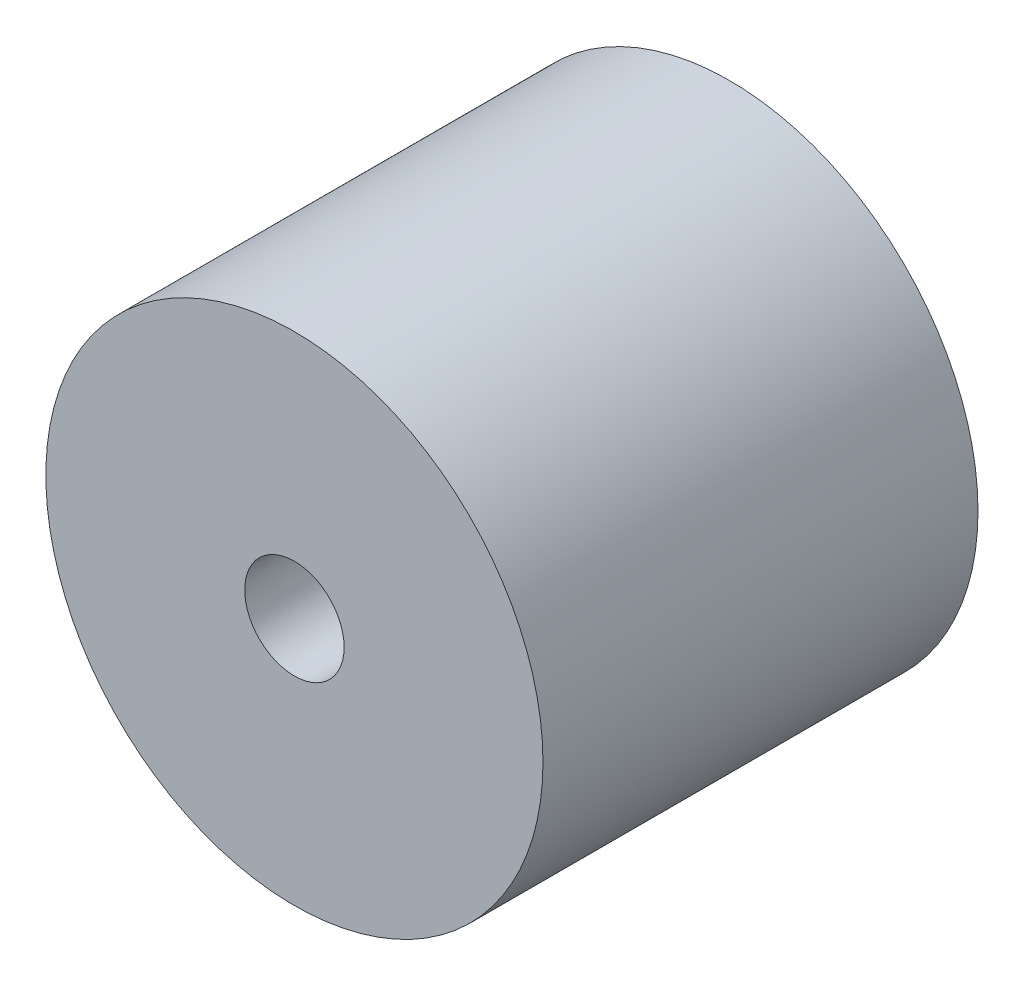
SolidWorks part; units mm, degrees
ref_plane "Front Plane" through (0, 0, 0) normal (0, 0, 1) x (1, 0, 0)
ref_plane "Top Plane" through (0, 0, 0) normal (0, 1, 0) x (1, 0, 0)
ref_plane "Right Plane" through (0, 0, 0) normal (1, 0, 0) x (0, 0, -1)
sketch "Sketch1" plane through (0, 0, 0) normal (1, 0, 0) x (0, 0, -1)
  line L0 (-110.9405, 0) -> (128.8814, 0) construction
  line L1 (55, 0) -> (-55, 0) construction
  line L2 (0, 55) -> (0, -55) construction
  line L3 (0, 0.4) -> (3.5, 0.4)
  line L4 (0, 0.4) -> (0, 2)
  line L5 (0, 2) -> (3.5, 2)
  line L6 (3.5, 0.4) -> (3.5, 2)
  dimension "D1" = 4
  dimension "D2" = 0.8
  dimension "D3" = 3.5
revolve "Revolve1" add sketch "Sketch1" angle 360 about L0
